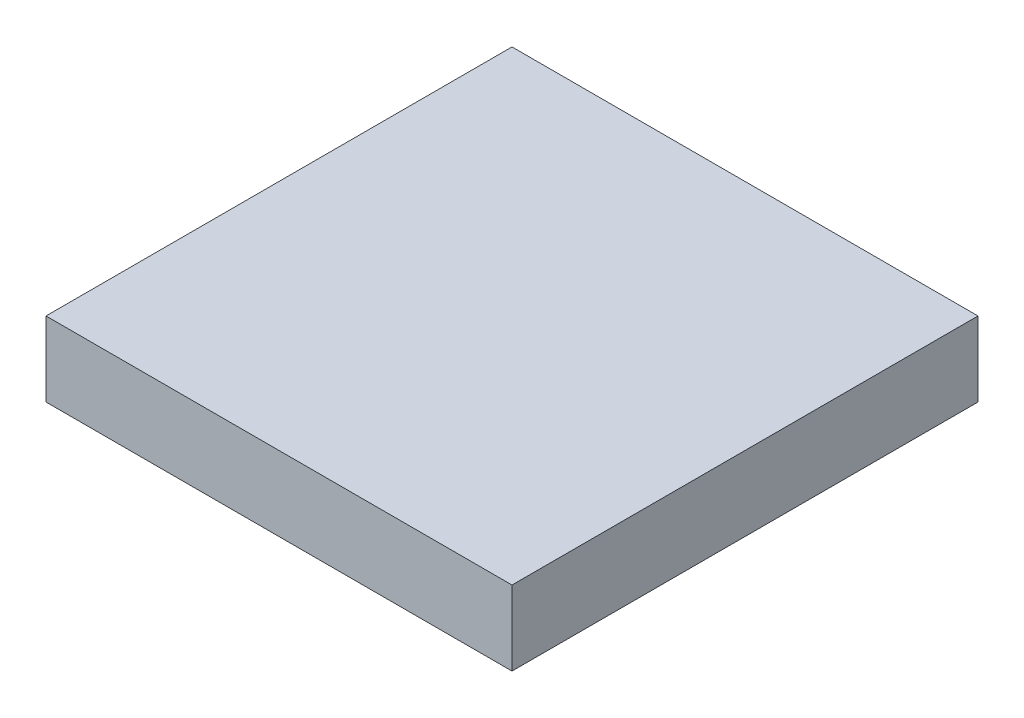
SolidWorks part; units mm, degrees
ref_plane "Plane1" through (0, 0, 0) normal (0, 0, 1) x (1, 0, 0)
ref_plane "Plane2" through (0, 0, 0) normal (0, 1, 0) x (1, 0, 0)
ref_plane "Plane3" through (0, 0, 0) normal (1, 0, 0) x (0, 0, -1)
other "Configuration Table"
sketch "Sketch1" plane through (0, 0, 0) normal (0, 0, 1) x (1, 0, 0)
  line L1 (0, 0) -> (50, 0)
  line L2 (0, 0) -> (0, 8)
  line L3 (0, 8) -> (50, 8)
  line L4 (50, 0) -> (50, 8)
  dimension "D1" = 8
  dimension "D2" = 50
extrude "Base-Extrude" add sketch "Sketch1" against normal blind 50
